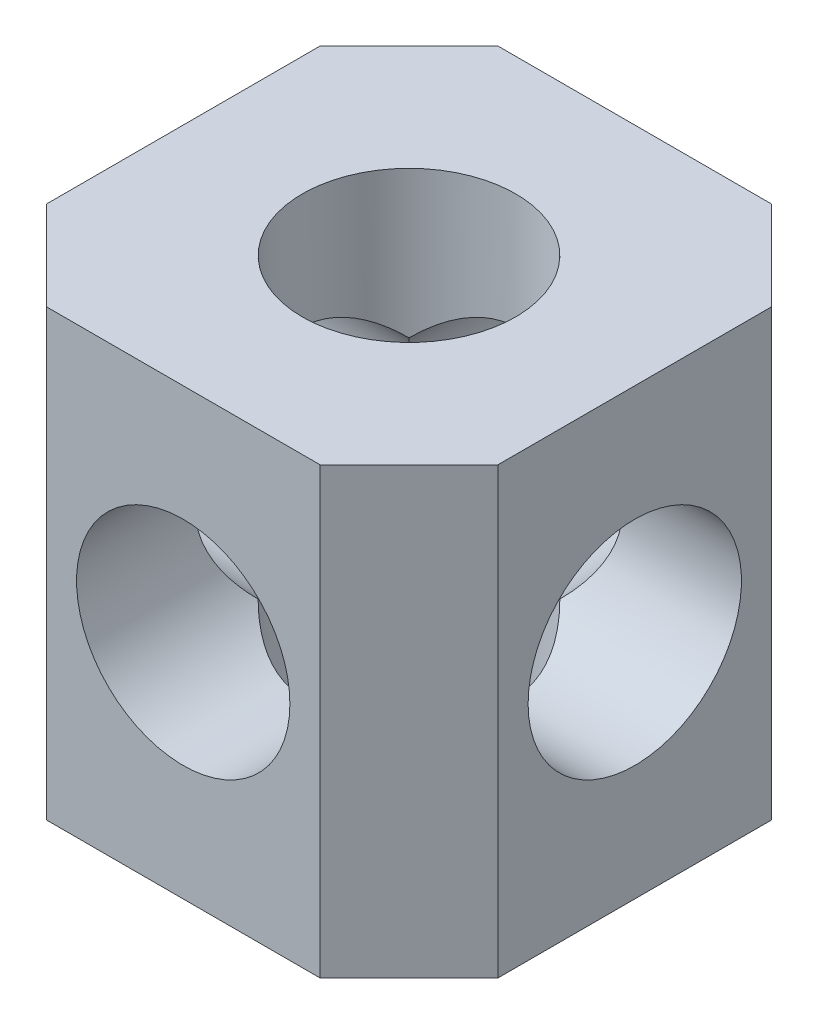
SolidWorks part; units mm, degrees
ref_plane "Front Plane" through (0, 0, 0) normal (0, 0, 1) x (1, 0, 0)
ref_plane "Top Plane" through (0, 0, 0) normal (0, 1, 0) x (1, 0, 0)
ref_plane "Right Plane" through (0, 0, 0) normal (1, 0, 0) x (0, 0, -1)
sketch "Sketch1" plane through (0, 0, 0) normal (0, 1, 0) x (1, 0, 0)
  line L0 (-7.7, 12.7) -> (-12.7, 7.7)
  line L5 (7.7, -12.7) -> (-7.7, -12.7)
  line L6 (12.7, -7.7) -> (12.7, 7.7)
  line L11 (7.7, 12.7) -> (-7.7, 12.7)
  line L12 (-12.7, -7.7) -> (-12.7, 7.7)
  line L13 (12.7, -12.7) -> (-12.7, 12.7) construction
  line L14 (12.7, 12.7) -> (-12.7, -12.7) construction
  line L19 (-7.7, -12.7) -> (-12.7, -7.7)
  line L20 (12.7, -7.7) -> (7.7, -12.7)
  line L21 (12.7, 7.7) -> (7.7, 12.7)
  circle A1 centre (0, 0) radius 6
  point P0 (0, 0)
  dimension "D3" = 12
  dimension "D1" = 25.4
  dimension "D2" = 25.4
extrude "Boss-Extrude1" add sketch "Sketch1" along normal blind 15
sketch "Sketch2" plane through (0, 0, 12.7) normal (0, 0, 1) x (1, 0, 0)
  line L0 (-7.7, 15) -> (7.7, 15) construction
  line L2 (-7.7, 0) -> (7.7, 0) construction
  circle A0 centre (0, 7.5) radius 6
  dimension "D1" = 12
  dimension "D2" = 15
  dimension "D3" = 7.5
extrude "Cut-Extrude1" cut sketch "Sketch2" against normal blind 32
sketch "Sketch3" plane through (-12.7, 0, 0) normal (-1, 0, 0) x (0, 0, 1)
  line L0 (-7.7, 0) -> (7.7, 0) construction
  circle A0 centre (0, 7.5) radius 6
  dimension "D1" = 12
  dimension "D2" = 7.5
extrude "Cut-Extrude2" cut sketch "Sketch3" against normal blind 32
sketch "Sketch6" plane through (0, 15, 0) normal (0, 1, 0) x (1, 0, 0)
  line L8 (7.7, 12.7) -> (-7.7, 12.7)
  line L9 (-7.7, 12.7) -> (-12.7, 7.7)
  line L10 (-12.7, 7.7) -> (-12.7, -7.7)
  line L11 (-12.7, -7.7) -> (-7.7, -12.7)
  line L12 (-7.7, -12.7) -> (7.7, -12.7)
  line L13 (7.7, -12.7) -> (12.7, -7.7)
  line L14 (12.7, -7.7) -> (12.7, 7.7)
  line L15 (12.7, 7.7) -> (7.7, 12.7)
  line L16 (7.7, 12.7) -> (-7.7, 12.7)
  line L17 (-7.7, 12.7) -> (-12.7, 7.7)
  line L18 (-12.7, 7.7) -> (-12.7, -7.7)
  line L19 (-12.7, -7.7) -> (-7.7, -12.7)
  line L20 (-7.7, -12.7) -> (7.7, -12.7)
  line L21 (7.7, -12.7) -> (12.7, -7.7)
  line L22 (12.7, -7.7) -> (12.7, 7.7)
  line L23 (12.7, 7.7) -> (7.7, 12.7)
  dimension "D1" = 0
extrude "Boss-Extrude2" add sketch "Sketch6" along normal blind 5
sketch "Sketch7" plane through (0, 0, 0) normal (0, -1, 0) x (1, 0, 0)
  line L8 (-7.7, -12.7) -> (7.7, -12.7)
  line L9 (7.7, -12.7) -> (12.7, -7.7)
  line L10 (12.7, -7.7) -> (12.7, 7.7)
  line L11 (12.7, 7.7) -> (7.7, 12.7)
  line L12 (7.7, 12.7) -> (-7.7, 12.7)
  line L13 (-7.7, 12.7) -> (-12.7, 7.7)
  line L14 (-12.7, 7.7) -> (-12.7, -7.7)
  line L15 (-12.7, -7.7) -> (-7.7, -12.7)
  line L16 (-7.7, -12.7) -> (7.7, -12.7)
  line L17 (7.7, -12.7) -> (12.7, -7.7)
  line L18 (12.7, -7.7) -> (12.7, 7.7)
  line L19 (12.7, 7.7) -> (7.7, 12.7)
  line L20 (7.7, 12.7) -> (-7.7, 12.7)
  line L21 (-7.7, 12.7) -> (-12.7, 7.7)
  line L22 (-12.7, 7.7) -> (-12.7, -7.7)
  line L23 (-12.7, -7.7) -> (-7.7, -12.7)
  dimension "D1" = 0
extrude "Boss-Extrude3" add sketch "Sketch7" along normal blind 5 contours L16 L17 L18 L19 L20 L21 L22 L23
sketch "Sketch8" plane through (0, 20, 0) normal (0, 1, 0) x (1, 0, 0)
  circle A0 centre (0, 0) radius 6
  dimension "D1" = 12
extrude "Cut-Extrude3" cut sketch "Sketch8" against normal blind 31
